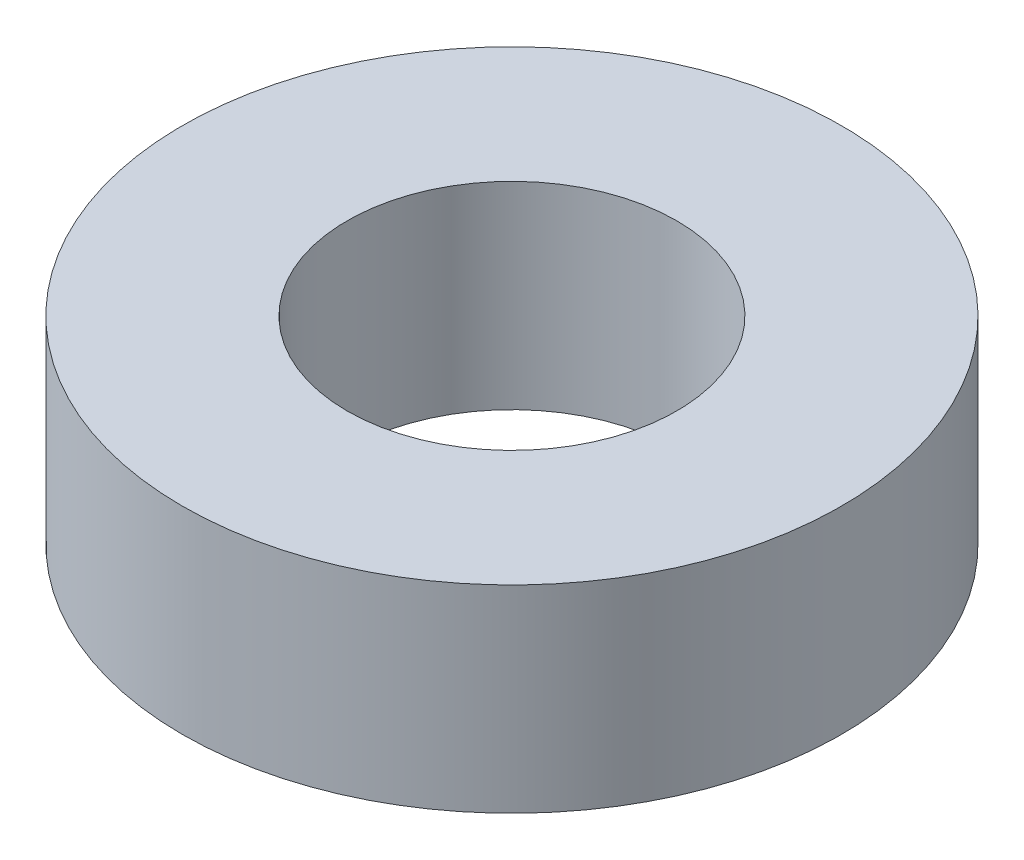
SolidWorks part; units mm, degrees
ref_plane "Front Plane" through (0, 0, 0) normal (0, 0, 1) x (1, 0, 0)
ref_plane "Top Plane" through (0, 0, 0) normal (0, 1, 0) x (1, 0, 0)
ref_plane "Right Plane" through (0, 0, 0) normal (1, 0, 0) x (0, 0, -1)
sketch "Sketch1" plane through (0, 0, 0) normal (0, 1, 0) x (1, 0, 0)
  circle A0 centre (0, 0) radius 5
  circle A1 centre (0, 0) radius 2.5
  dimension "D1" = 5
  dimension "D2" = 10
extrude "Boss-Extrude1" add sketch "Sketch1" along normal mid plane 3
